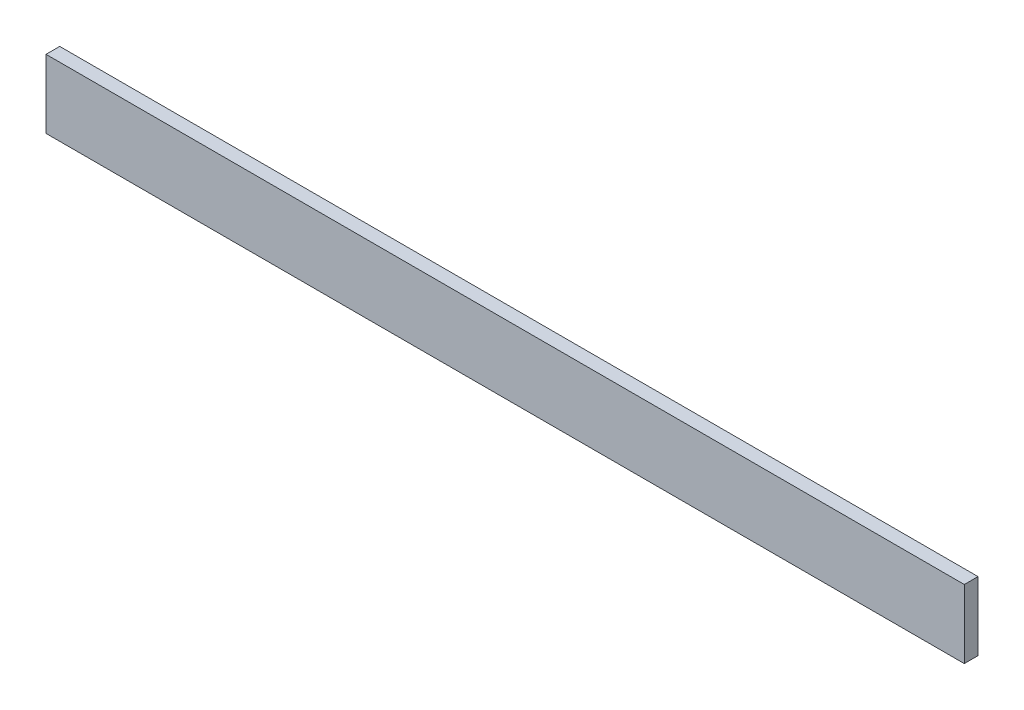
SolidWorks part; units mm, degrees
ref_plane "Front Plane" through (0, 0, 0) normal (0, 0, 1) x (1, 0, 0)
ref_plane "Top Plane" through (0, 0, 0) normal (0, 1, 0) x (1, 0, 0)
ref_plane "Right Plane" through (0, 0, 0) normal (1, 0, 0) x (0, 0, -1)
sketch "Sketch1" plane through (0, 0, 0) normal (0, 0, 1) x (1, 0, 0)
  line L1 (0, 0) -> (850.9, 0)
  line L2 (0, 0) -> (0, 63.5)
  line L3 (0, 63.5) -> (850.9, 63.5)
  line L4 (850.9, 0) -> (850.9, 63.5)
  dimension "D1" = 850.9
  dimension "D2" = 63.5
extrude "Boss-Extrude1" add sketch "Sketch1" along normal blind 12.7
